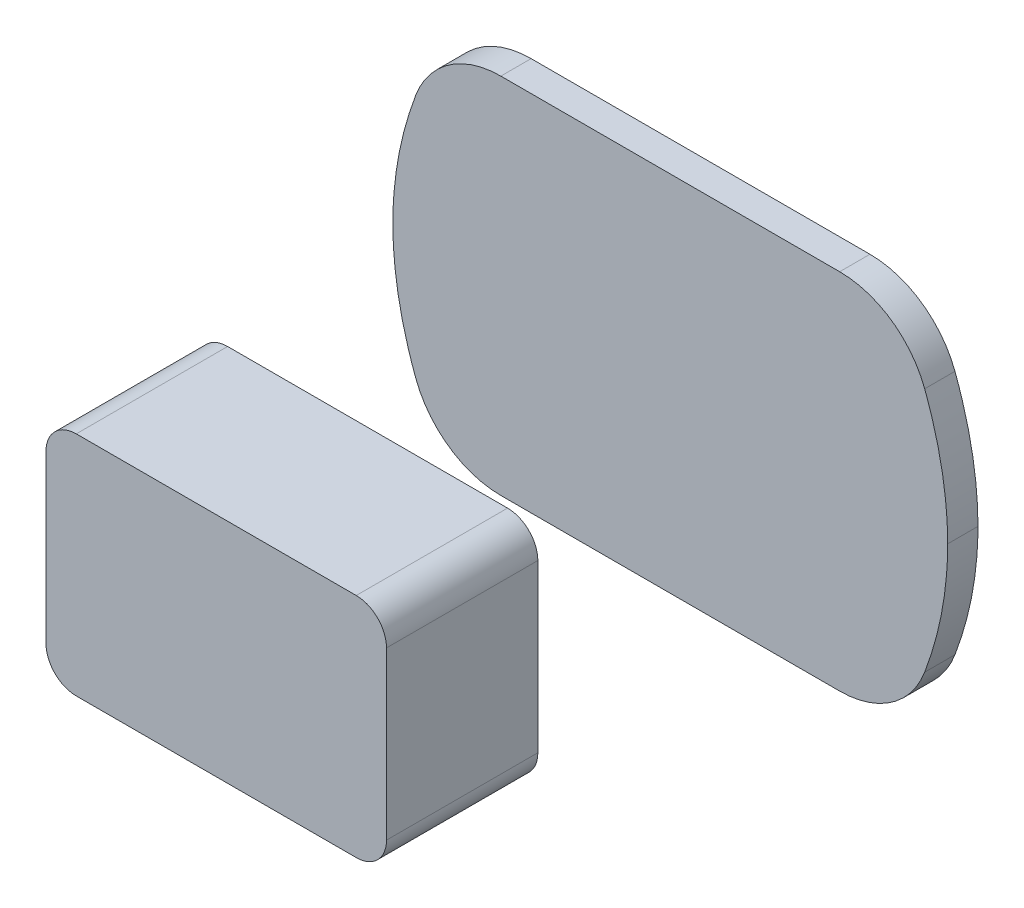
SolidWorks part; units mm, degrees
ref_plane "Front Plane" through (0, 0, 0) normal (0, 0, 1) x (1, 0, 0)
ref_plane "Top Plane" through (0, 0, 0) normal (0, 1, 0) x (1, 0, 0)
ref_plane "Right Plane" through (0, 0, 0) normal (1, 0, 0) x (0, 0, -1)
sketch "Sketch1" plane through (0, 0, 0) normal (0, 0, 1) x (1, 0, 0)
  line L18 (-15, 10) -> (-14.2911, 9.5274) construction
  line L19 (-11.1948, 12) -> (11.1948, 12)
  line L20 (-15.4079, 10.272) -> (-14.2911, 9.5274) construction
  line L21 (0, -12) -> (0, 12) construction
  line L22 (-18.3347, 0) -> (18.3347, 0) construction
  line L24 (15.4079, 10.272) -> (14.2911, 9.5274) construction
  line L25 (15, 10) -> (14.2911, 9.5274) construction
  line L29 (15, -10) -> (14.2911, -9.5274) construction
  line L30 (15.4079, -10.272) -> (14.2911, -9.5274) construction
  line L32 (-15.4079, -10.272) -> (-14.2911, -9.5274) construction
  line L33 (-15, -10) -> (-14.2911, -9.5274) construction
  line L35 (-11.1948, -12) -> (11.1948, -12)
  arc A1 (-11.1948, 12) -> (-16.8117, 8.1097) centre (-11.1948, 6) ccw
  arc A2 (11.1948, 12) -> (16.8117, 8.1097) centre (11.1948, 6) cw
  arc A5 (11.1948, -12) -> (16.8117, -8.1097) centre (11.1948, -6) ccw
  arc A6 (-11.1948, -12) -> (-16.8117, -8.1097) centre (-11.1948, -6) cw
  spline S0 degree 3 poles (-18.3347, 0) (-18.3272, 2.7261) (-17.8195, 5.4265) (-16.8117, 8.1097) knots 0.502499 0.502499 0.502499 0.502499 0.837905 0.837905 0.837905 0.837905
  spline S1 degree 3 poles (18.3347, 0) (18.3272, 2.7261) (17.8195, 5.4265) (16.8117, 8.1097) knots 0.502499 0.502499 0.502499 0.502499 0.837905 0.837905 0.837905 0.837905
  spline S2 degree 3 poles (18.3347, 0) (18.3272, -2.7261) (17.8195, -5.4265) (16.8117, -8.1097) knots 0.502499 0.502499 0.502499 0.502499 0.837905 0.837905 0.837905 0.837905
  spline S3 degree 3 poles (-18.3347, 0) (-18.3272, -2.7261) (-17.8195, -5.4265) (-16.8117, -8.1097) knots 0.502499 0.502499 0.502499 0.502499 0.837905 0.837905 0.837905 0.837905
  point P0 (0, 0)
  point P4 (-15, 0)
  point P10 (0, 0)
  point P11 (-11.0472, 7.3648)
  point P19 (0, 0)
  point P27 (-18.3347, 0)
  point P29 (-15, 0)
  point P30 (-15, 0)
  point P31 (11.0472, -7.3648)
  point P32 (0, 0)
  point P33 (-36.8928, -37.8819)
  point P34 (0, 0)
  point P35 (-15, 0)
  point P46 (0, 10)
  point P47 (11.0472, 7.3648)
  point P52 (0, 0)
  point P68 (15, 0)
  point P69 (0, -10)
  point P70 (-11.0472, -7.3648)
  point P71 (0, 0)
  dimension "D3" = 13.9635
  dimension "D6" = 3.8903
  dimension "D2" = 6
  dimension "D7" = 3.3347
  dimension "D10" = 3.3347
  dimension "D5" = 1.523
  dimension "D4" = 8.2959
ref_plane "Plane1" through (0, 0, 20) normal (0, 0, 1) x (1, 0, 0)
ref_plane "Plane2" through (0, 0, 30) normal (0, 0, 1) x (1, 0, 0)
sketch "Sketch6" plane through (0, 0, 20) normal (0, 0, 1) x (1, 0, 0)
  line L0 (-9.25, -7.5) -> (9.25, -7.5)
  line L1 (-11.25, -5.5) -> (-11.25, 5.5)
  line L2 (-9.25, 7.5) -> (9.25, 7.5)
  line L3 (11.25, -5.5) -> (11.25, 5.5)
  line L4 (-11.25, -7.5) -> (11.25, 7.5) construction
  line L5 (-11.25, 7.5) -> (11.25, -7.5) construction
  arc A0 (11.25, -5.5) -> (9.25, -7.5) centre (9.25, -5.5) cw
  arc A1 (9.25, 7.5) -> (11.25, 5.5) centre (9.25, 5.5) cw
  arc A2 (-11.25, -5.5) -> (-9.25, -7.5) centre (-9.25, -5.5) ccw
  arc A3 (-9.25, 7.5) -> (-11.25, 5.5) centre (-9.25, 5.5) ccw
  point P0 (0, 0)
  dimension "D3" = 2
  dimension "D1" = 15
  dimension "D2" = 22.5
extrude "Boss-Extrude1" add sketch "Sketch6" along normal blind 10
ref_plane "Plane3" through (0, 0, 27.8) normal (0, 0, 1) x (1, 0, 0)
sketch "Sketch7" plane through (0, 0, 27.8) normal (0, 0, 1) x (1, 0, 0)
  line L0 (-8.6337, -5.4044) -> (8.6337, -5.4044)
  line L1 (-8.6337, -5.4044) -> (-8.6337, 5.4044)
  line L2 (-8.6337, 5.4044) -> (8.6337, 5.4044)
  line L3 (8.6337, -5.4044) -> (8.6337, 5.4044)
  line L4 (-8.6337, -5.4044) -> (8.6337, 5.4044) construction
  line L5 (-8.6337, 5.4044) -> (8.6337, -5.4044) construction
  line L6 (9.25, 7.5) -> (-9.25, 7.5) construction
  line L7 (9.25, -7.5) -> (-9.25, -7.5)
  line L8 (11.25, -5.5) -> (11.25, 5.5)
  line L9 (9.25, 7.5) -> (-9.25, 7.5)
  line L10 (-11.25, -5.5) -> (-11.25, 5.5)
  line L11 (-9.25, -7.5) -> (9.25, -7.5) construction
  line L12 (11.25, -5.5) -> (11.25, 5.5) construction
  line L13 (-11.25, 5.5) -> (-11.25, -5.5) construction
  arc A0 (-11.25, 5.5) -> (-9.25, 7.5) centre (-9.25, 5.5) cw
  arc A1 (11.25, -5.5) -> (9.25, -7.5) centre (9.25, -5.5) cw
  arc A2 (9.25, 7.5) -> (11.25, 5.5) centre (9.25, 5.5) cw
  arc A3 (-9.25, -7.5) -> (-11.25, -5.5) centre (-9.25, -5.5) cw
  point P0 (0, 0)
  dimension "D1" = 2
  dimension "D2" = 2
extrude "Boss-Extrude2" add sketch "Sketch7" against normal blind 2
extrude "Boss-Extrude7" add sketch "Sketch1" against normal blind 2
sketch "Sketch19" plane through (0, 0, 27.8) normal (0, 0, 1) x (1, 0, 0)
  line L0 (-8.8467, -6.8353) -> (8.8467, -6.8353)
  line L1 (-8.8467, -6.8353) -> (-8.8467, -3.5368)
  line L2 (-8.8467, 6.8353) -> (8.8467, 6.8353)
  line L3 (8.8467, -6.8353) -> (8.8467, 6.8353)
  line L4 (-8.8467, -6.8353) -> (8.8467, 6.8353) construction
  line L5 (-8.8467, 6.8353) -> (8.8467, -6.8353) construction
  line L6 (-9.25, -7.5) -> (9.25, -7.5)
  line L7 (-11.25, -5.5) -> (-11.25, 5.5)
  line L8 (-9.25, 7.5) -> (9.25, 7.5)
  line L9 (11.25, -5.5) -> (11.25, 5.5)
  line L10 (-11.25, -7.5) -> (11.25, 7.5) construction
  line L11 (-11.25, 7.5) -> (11.25, -7.5) construction
  line L12 (-11.25, 5.5) -> (-11.25, -5.5) construction
  line L13 (11.25, -5.5) -> (11.25, 5.5) construction
  line L14 (-9.25, -7.5) -> (9.25, -7.5) construction
  line L15 (9.25, 7.5) -> (-9.25, 7.5) construction
  line L16 (-8.8467, 3.2996) -> (-10.8779, 3.2996)
  line L18 (-10.8779, -3.5368) -> (-8.8467, -3.5368)
  line L19 (-8.8467, 3.2996) -> (-8.8467, 6.8353)
  line L20 (-10.8779, 3.2996) -> (-10.8779, -3.5368)
  arc A0 (11.25, -5.5) -> (9.25, -7.5) centre (9.25, -5.5) cw
  arc A1 (9.25, 7.5) -> (11.25, 5.5) centre (9.25, 5.5) cw
  arc A2 (-11.25, -5.5) -> (-9.25, -7.5) centre (-9.25, -5.5) ccw
  arc A3 (-9.25, 7.5) -> (-11.25, 5.5) centre (-9.25, 5.5) ccw
  point P0 (0, 0)
  point P7 (0, 0)
  dimension "D3" = 2
extrude "Boss-Extrude9" add sketch "Sketch19" against normal blind 2
